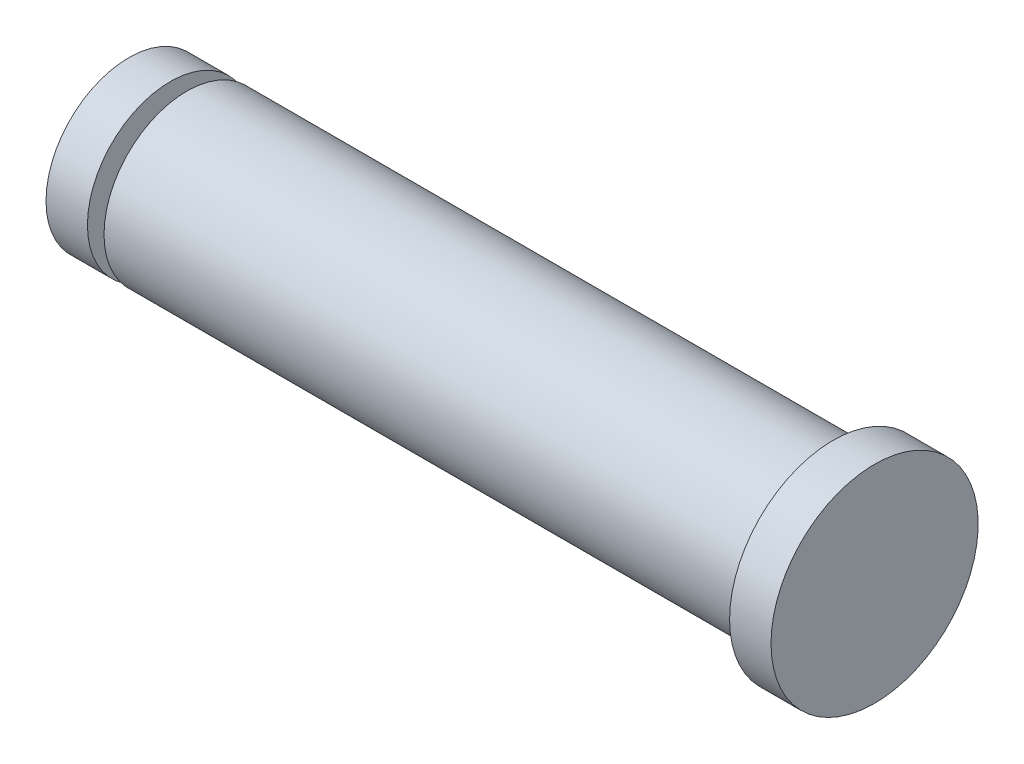
SolidWorks part; units mm, degrees
ref_plane "前视基准面" through (0, 0, 0) normal (0, 0, 1) x (1, 0, 0)
ref_plane "上视基准面" through (0, 0, 0) normal (0, 1, 0) x (1, 0, 0)
ref_plane "右视基准面" through (0, 0, 0) normal (1, 0, 0) x (0, 0, -1)
sketch "草图1" plane through (0, 0, 0) normal (0, 0, 1) x (1, 0, 0)
  line L0 (0, 0) -> (270, 0)
  line L1 (21, 30) -> (255, 30)
  line L2 (255, 30) -> (255, 37.5)
  line L3 (255, 37.5) -> (270, 37.5)
  line L4 (270, 37.5) -> (270, 0)
  line L5 (21, 30) -> (21, 20)
  line L6 (21, 20) -> (15, 20)
  line L7 (15, 20) -> (15, 30)
  line L8 (15, 30) -> (0, 30)
  line L9 (0, 30) -> (0, 0)
  dimension "D1" = 270
  dimension "D2" = 234
  dimension "D3" = 30
  dimension "D4" = 37.5
  dimension "D5" = 15
  dimension "D6" = 6
  dimension "D7" = 20
revolve "旋转1" add sketch "草图1" angle 360 about L0
